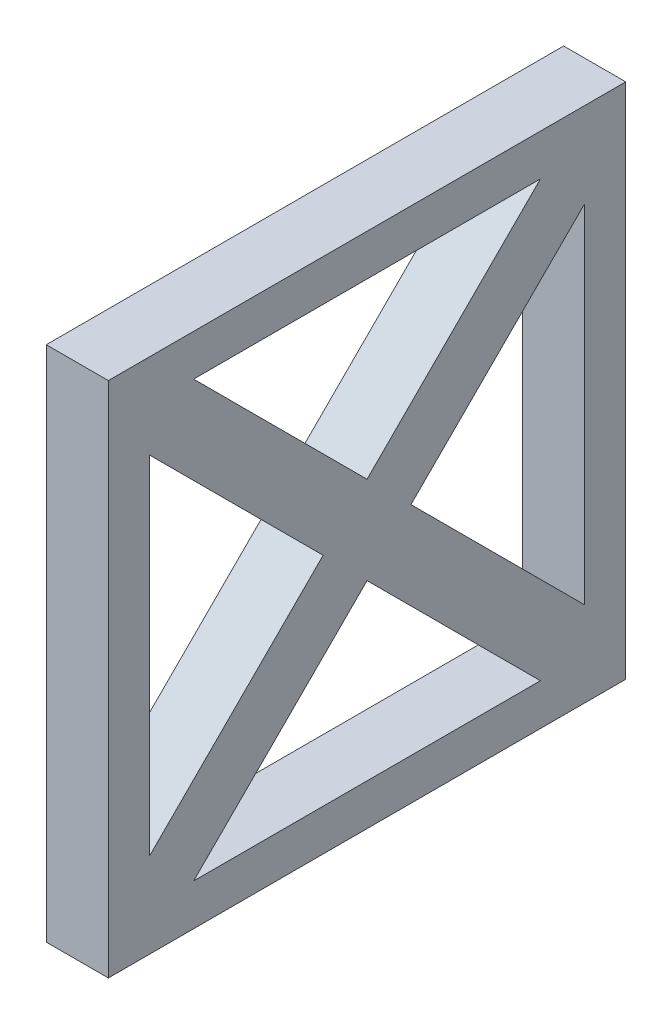
SolidWorks part; units mm, degrees
material "Balsa"
ref_plane "Front Plane" through (0, 0, 0) normal (1, 0, 0) x (0, 1, 0)
ref_plane "Top Plane" through (0, 0, 0) normal (0, 0, 1) x (0, 1, 0)
ref_plane "Right Plane" through (0, 0, 0) normal (0, 1, 0) x (-1, 0, 0)
sketch "Sketch1" plane through (0, 0, 0) normal (1, 0, 0) x (0, 1, 0)
  line L0 (21, 16.7574) -> (-16.7574, -21)
  line L5 (-21, -21) -> (21, -21)
  line L6 (-21, -21) -> (-21, 21)
  line L11 (-21, 21) -> (21, 21)
  line L12 (21, -21) -> (21, 21)
  line L13 (-21, -21) -> (21, 21) construction
  line L14 (-21, 21) -> (21, -21) construction
  line L15 (16.7574, 21) -> (-21, -16.7574)
  line L16 (0, -21) -> (0, 21) construction
  line L18 (-16.7574, 21) -> (21, -16.7574)
  line L19 (-21, 16.7574) -> (16.7574, -21)
  line L20 (-25, -25) -> (-25, 25)
  line L21 (-25, 25) -> (25, 25)
  line L22 (25, -25) -> (25, 25)
  line L23 (-25, -25) -> (25, -25)
  point P0 (0, 0)
  dimension "D1" = 50
  dimension "D2" = 50
  dimension "D3" = 3
  dimension "D4" = 3
  dimension "D5" = 4
extrude "Boss-Extrude1" add sketch "Sketch1" along normal blind 6
